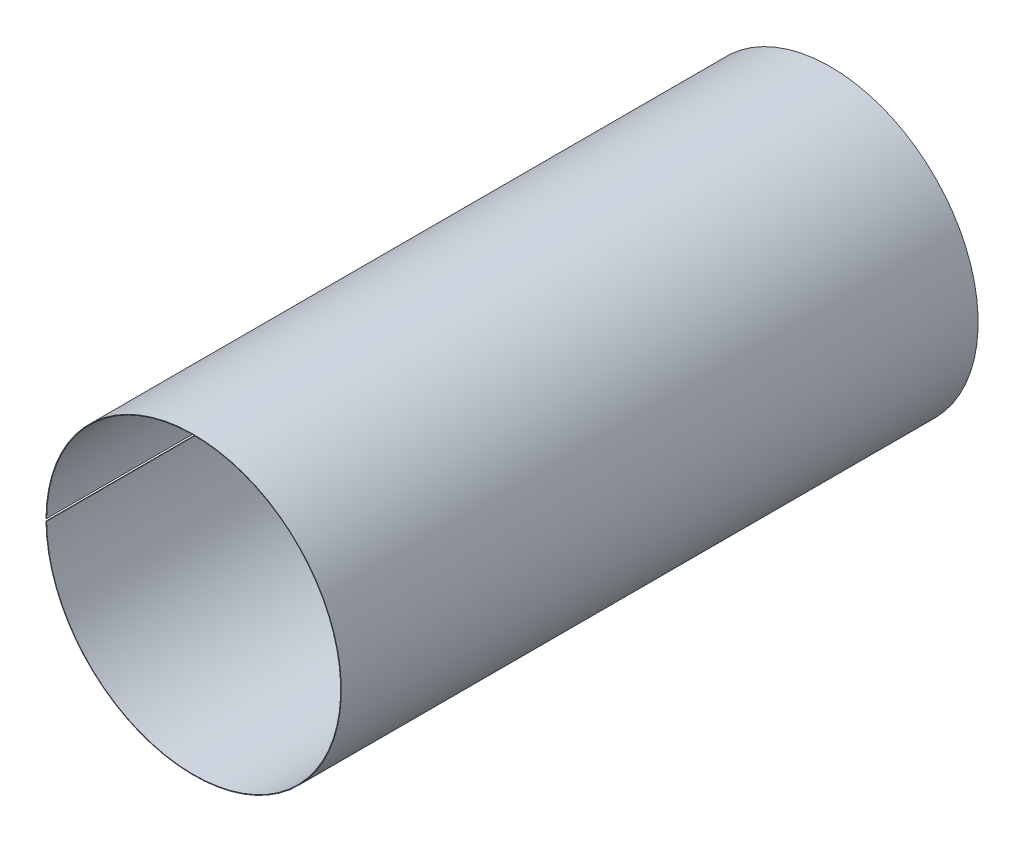
SolidWorks part; units mm, degrees
ref_plane "Front" through (0, 0, 0) normal (0, 0, 1) x (1, 0, 0)
ref_plane "Top" through (0, 0, 0) normal (0, 1, 0) x (1, 0, 0)
ref_plane "Right" through (0, 0, 0) normal (1, 0, 0) x (0, 0, -1)
sketch "Sketch2" plane through (0, 0, 0) normal (0, 0, 1) x (1, 0, 0)
  circle A0 centre (0, 0) radius 64.77
  circle A1 centre (0, 0) radius 64.516
  dimension "D1" = 129.54
  dimension "D2" = 129.032
extrude "Boss-Extrude1" add sketch "Sketch2" along normal blind 279.4
sketch "Sketch3" plane through (0, 0, 279.4) normal (0, 0, 1) x (1, 0, 0)
  line L0 (-71.4518, 0) -> (70.1682, 0) construction
  line L1 (0, 68.3498) -> (0, -67.2802) construction
ref_plane "Plane1" through (-64.77, 0, 0) normal (-1, 0, 0) x (0, 0, 1)
sketch "Sketch5" plane through (-64.77, 0, 0) normal (-1, 0, 0) x (0, 0, 1)
  line L0 (-8.3863, 0) -> (289.133, 0) construction
  line L1 (0, 0.508) -> (279.4, 0.508)
  line L2 (0, 64.77) -> (0, -64.77) construction
  line L3 (279.4, 68.3498) -> (279.4, -67.2802) construction
  line L4 (279.4, 0.508) -> (279.4, -0.508)
  line L5 (0, 0.508) -> (0, -0.508)
  line L6 (0, -0.508) -> (279.4, -0.508)
  point P12 (279.4, 0)
  point P13 (0, 0)
  dimension "D1" = 0.508
extrude "Cut-Extrude1" cut sketch "Sketch5" against normal up to next
